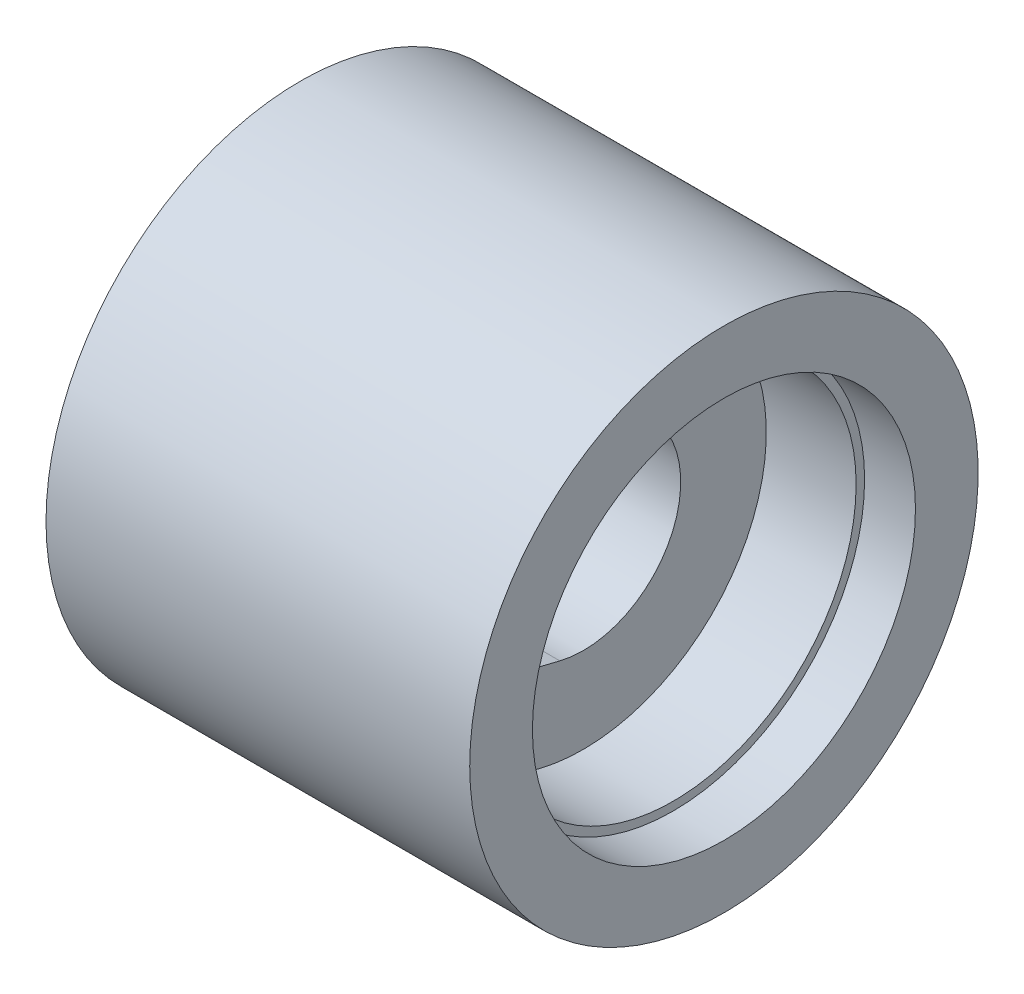
SolidWorks part; units mm, degrees
ref_plane "前视基准面" through (0, 0, 0) normal (0, 0, 1) x (1, 0, 0)
ref_plane "上视基准面" through (0, 0, 0) normal (0, 1, 0) x (1, 0, 0)
ref_plane "右视基准面" through (0, 0, 0) normal (1, 0, 0) x (0, 0, -1)
sketch "Sketch1" plane through (0, 0, 0) normal (0, 0, 1) x (1, 0, 0)
  line L0 (0, 0) -> (251.577, 0) construction
  line L1 (0, 0) -> (0, 113) construction
  line L2 (0, 113) -> (-30, 113)
  line L3 (-30, 113) -> (-30, 108)
  line L4 (-30, 108) -> (-83, 108)
  line L5 (-83, 108) -> (-83, 57.5)
  line L6 (-83, 57.5) -> (-250, 57.5)
  line L7 (-250, 57.5) -> (-250, 0) construction
  line L8 (-250, 0) -> (0, 0) construction
  line L9 (0, 113) -> (0, 150)
  line L10 (0, 150) -> (-250, 150)
  line L11 (-250, 150) -> (-250, 57.5)
  dimension "D1" = 226
  dimension "D2" = 216
  dimension "D3" = 115
  dimension "D4" = 30
  dimension "D5" = 83
  dimension "D6" = 250
  dimension "D7" = 300
revolve "Revolve1" add sketch "Sketch1" angle 360 about L0
sketch "Sketch2" plane through (-250, 0, 0) normal (-1, 0, 0) x (0, 0, 1)
  line L0 (13.8, -55.8194) -> (108.04, -32.5209)
  line L1 (13.8, 55.8194) -> (108.04, 32.5209)
  line L2 (0, 0) -> (100, 0) construction
  arc A0 (108.04, -32.5209) -> (108.04, 32.5209) centre (100, 0) ccw
  circle A1 centre (0, 0) radius 57.5 construction
  arc A2 (13.8, 55.8194) -> (13.8, -55.8194) centre (0, 0) cw
  dimension "D1" = 67
  dimension "D3" = 57.5
  dimension "D2" = 100
extrude "Extrude1" cut sketch "Sketch2" against normal up to surface (167 mm away) up to face at (-83, 0, 108)
sketch "Sketch5" plane through (0, 0, 0) normal (0, 0, 1) x (1, 0, 0)
  line L0 (0, 100) -> (157.9794, 100) construction
  line L1 (0, -150) -> (0, 150) construction
  line L2 (0, 0) -> (-250, 0) construction
  line L4 (0, 0) -> (0, 177.7863) construction
  line L5 (-125, 135.5) -> (-262.5372, 135.5)
  line L6 (-262.5372, 135.5) -> (-262.5372, 100)
  line L7 (-262.5372, 100) -> (-106, 100)
  line L9 (-125, 127.5) -> (-122, 127.5)
  line L10 (-122, 127.5) -> (-122, 128.5)
  line L11 (-122, 128.5) -> (-121, 128.5)
  line L12 (-121, 128.5) -> (-121, 127.5)
  line L13 (-121, 127.5) -> (-108, 127.5)
  line L14 (-108, 127.5) -> (-108, 125)
  line L15 (-108, 125) -> (-106, 125)
  line L16 (-106, 125) -> (-106, 100)
  line L17 (-125, 135.5) -> (-125, 127.5)
  dimension "D1" = 100
  dimension "D2" = 125
  dimension "D3" = 3
  dimension "D4" = 1
  dimension "D5" = 71
  dimension "D6" = 55
  dimension "D7" = 13
  dimension "D8" = 50
  dimension "D9" = 2
revolve "Cut-Revolve1" cut sketch "Sketch5" angle 360 about L7
sketch "Sketch6" plane through (-250, 0, 0) normal (-1, 0, 0) x (0, 0, 1)
  line L0 (-34.6302, 107.81) -> (-56.0912, 12.65)
  line L1 (0, 100) -> (0, 0) construction
  line L2 (34.6302, 107.81) -> (56.0912, 12.65)
  arc A0 (-56.0912, 12.65) -> (56.0912, 12.65) centre (0, 0) ccw
  arc A1 (34.6302, 107.81) -> (-34.6302, 107.81) centre (0, 100) ccw
  dimension "D1" = 115
  dimension "D2" = 71
extrude "Extrude2" cut sketch "Sketch6" against normal up to surface (125 mm away) up to face at (-125, 100, 35.5)
sketch "Sketch7" plane through (0, 0, 0) normal (0, 1, 0) x (1, 0, 0)
  line L0 (0, 0) -> (205.7427, 0) construction
  line L1 (0, 0) -> (0, 204.3465) construction
  line L2 (-250, 135.5) -> (-173, 135.5)
  line L3 (-173, 135.5) -> (-173, 127.5)
  line L4 (-173, 127.5) -> (-170, 127.5)
  line L5 (-170, 127.5) -> (-170, 128.5)
  line L6 (-170, 128.5) -> (-169, 128.5)
  line L7 (-169, 128.5) -> (-169, 127.5)
  line L8 (-169, 127.5) -> (-156, 127.5)
  line L9 (-156, 127.5) -> (-156, 125)
  line L10 (-156, 125) -> (-154, 125)
  line L11 (-154, 125) -> (-154, 100)
  line L14 (-154, 100) -> (-250, 100)
  line L15 (-250, 100) -> (-250, 135.5)
  line L16 (-154, 100) -> (11.2471, 100) construction
  line L17 (-250, 150) -> (-250, -150) construction
  dimension "D1" = 100
  dimension "D2" = 50
  dimension "D3" = 55
  dimension "D4" = 2
  dimension "D5" = 1
  dimension "D6" = 3
  dimension "D7" = 71
  dimension "D8" = 173
  dimension "D9" = 13
revolve "Cut-Revolve2" cut sketch "Sketch7" angle 360 about L14
sketch "Sketch8" plane through (-250, 0, 0) normal (-1, 0, 0) x (0, 0, 1)
  line L0 (-100, 0) -> (0, 0) construction
  line L1 (-107.81, 34.6302) -> (-12.65, 56.0912)
  line L2 (-107.81, -34.6302) -> (-12.65, -56.0912)
  circle A0 centre (-100, 0) radius 35.5 construction
  arc A1 (-107.81, 34.6302) -> (-107.81, -34.6302) centre (-100, 0) ccw
  arc A2 (-12.65, -56.0912) -> (-12.65, 56.0912) centre (0, 0) ccw
  dimension "D1" = 115
extrude "Extrude3" cut sketch "Sketch8" against normal up to surface (77 mm away) up to face at (-173, 0, -135.5)
ref_plane "Plane2" through (0, -150, 0) normal (0, -1, 0) x (-1, 0, 0)
sketch "Sketch10" plane through (0, -150, 0) normal (0, -1, 0) x (-1, 0, 0)
  line L0 (250, 0) -> (0, 0) construction
  line L1 (250, -150) -> (250, 150) construction
  circle A0 centre (125, 0) radius 15
  dimension "D1" = 30
extrude "Extrude4" cut sketch "Sketch10" against normal blind 1
sketch "Sketch11" plane through (-250, 0, 0) normal (-1, 0, 0) x (0, 0, 1)
  point P0 (0, 0)
